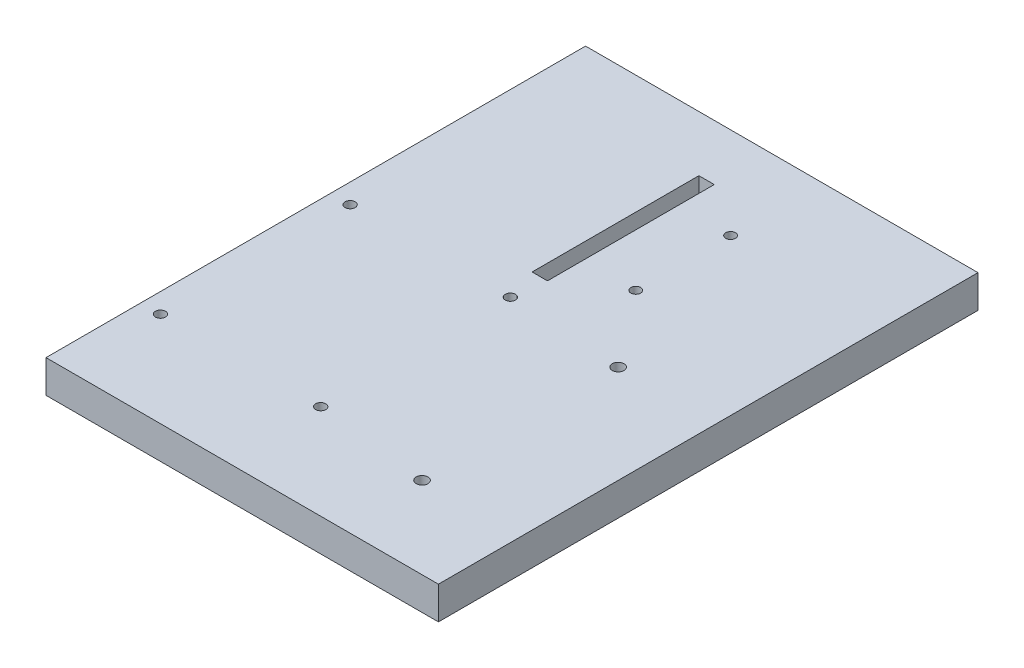
SolidWorks part; units mm, degrees
ref_plane "Front Plane" through (0, 0, 0) normal (0, 0, 1) x (1, 0, 0)
ref_plane "Top Plane" through (0, 0, 0) normal (0, 1, 0) x (1, 0, 0)
ref_plane "Right Plane" through (0, 0, 0) normal (1, 0, 0) x (0, 0, -1)
sketch "Sketch1" plane through (0, 0, 0) normal (0, 1, 0) x (1, 0, 0)
  line L1 (0, 0) -> (120, 0)
  line L2 (0, 0) -> (0, 165)
  line L3 (0, 165) -> (120, 165)
  line L4 (120, 0) -> (120, 165)
  dimension "D1" = 120
  dimension "D2" = 165
extrude "Base" add sketch "Sketch1" along normal blind 10
hole_wizard "Pi-MountHoles" positions "Sketch13" profile "Sketch14" counterbore size "M2.5" standard "ANSI Metric" end condition up to next
sketch "Sketch13" plane through (0, 0, 0) normal (0, -1, 0) x (-1, 0, 0)
  line L1 (0, 0) -> (-120, 0) construction
  line L2 (0, 165) -> (0, 0) construction
  point P0 (-6, 29)
  point P2 (-55, 29)
  point P4 (-55, 87)
  point P6 (-6, 87)
  dimension "D1" = 49
  dimension "D2" = 58
  dimension "D3" = 87
  dimension "D4" = 6
sketch "Sketch14" plane through (6, 0, -29) normal (1, 0, 0) x (0, 0, -1)
  line L0 (0, 0) -> (0, 10)
  line L1 (0, 10) -> (1.55, 10)
  line L3 (1.55, 10) -> (1.55, 2.1)
  line L4 (3, 2.1) -> (1.55, 2.1)
  line L5 (3, 2.1) -> (3, 0.025)
  line L6 (3, 0.025) -> (3.025, 0)
  line L7 (3.025, 0) -> (0, 0)
  line L8 (-3, 0.025) -> (-3.025, 0) construction
  line L11 (0, -6.35) -> (0, 107.95) construction
  dimension "Thru Hole Dia." = 3.1
  dimension "Thru Hole Depth" = 10
  dimension "C'Bore Dia." = 6
  dimension "C'Bore Depth" = 2.1
  dimension "Near C'Sink Dia." = 6.05
  dimension "Near C'Sink Angle" = 90
hole_wizard "Battery-MountHoles" positions "Sketch15" profile "Sketch16" counterbore size "M3" standard "ANSI Metric" end condition up to next
sketch "Sketch15" plane through (0, 0, 0) normal (0, -1, 0) x (-1, 0, 0)
  line L0 (0, 0) -> (-120, 0) construction
  circle A0 centre (-55, 87) radius 1.55 construction
  point P0 (-90, 25)
  point P2 (-90, 84.95)
  dimension "D1" = 59.95
  dimension "D2" = 25
  dimension "D3" = 35
sketch "Sketch16" plane through (90, 0, -25) normal (1, 0, 0) x (0, 0, -1)
  line L0 (0, 0) -> (0, 10)
  line L1 (0, 10) -> (1.8, 10)
  line L3 (1.8, 10) -> (1.8, 2.4)
  line L4 (3.5, 2.4) -> (1.8, 2.4)
  line L5 (3.5, 2.4) -> (3.5, 0.025)
  line L6 (3.5, 0.025) -> (3.525, 0)
  line L7 (3.525, 0) -> (0, 0)
  line L8 (-3.5, 0.025) -> (-3.525, 0) construction
  line L11 (0, -6.35) -> (0, 107.95) construction
  dimension "Thru Hole Dia." = 3.6
  dimension "Thru Hole Depth" = 10
  dimension "C'Bore Dia." = 7
  dimension "C'Bore Depth" = 2.4
  dimension "Near C'Sink Dia." = 7.05
  dimension "Near C'Sink Angle" = 90
sketch "Sketch17" plane through (0, 10, 0) normal (0, 1, 0) x (1, 0, 0)
  line L1 (51.65, 148) -> (56.35, 148)
  line L2 (51.65, 148) -> (51.65, 97)
  line L3 (51.65, 97) -> (56.35, 97)
  line L4 (56.35, 148) -> (56.35, 97)
  circle A4 centre (55, 87) radius 1.55 construction
  dimension "D1" = 3.35
  dimension "D4" = 10
  dimension "D2" = 4.7
  dimension "D3" = 51
extrude "StepperBracketSlot" cut sketch "Sketch17" against normal up to surface (10 mm away) up to face at (90, 0, -28.525)
sketch "Sketch18" plane through (0, 10, 0) normal (0, 1, 0) x (1, 0, 0)
  line L1 (56.35, 97) -> (56.35, 148) construction
  circle A0 centre (72.35, 137) radius 1.5
  circle A1 centre (72.35, 108) radius 1.5
  point P4 (0, 0)
  point P5 (0, 0)
  point P6 (0, 0)
  point P7 (0, 0)
  point P10 (56.35, 122.5)
  point P11 (0, 0)
  dimension "D1" = 3
  dimension "D2" = 29
  dimension "D3" = 14.5
  dimension "D4" = 16
extrude "AngleBracket-MountHoles" cut sketch "Sketch18" against normal up to surface (10 mm away) up to face at (54, 0, -122.5)
equation "\"D3@Sketch18\"=\"D2@Sketch18\"/2"
